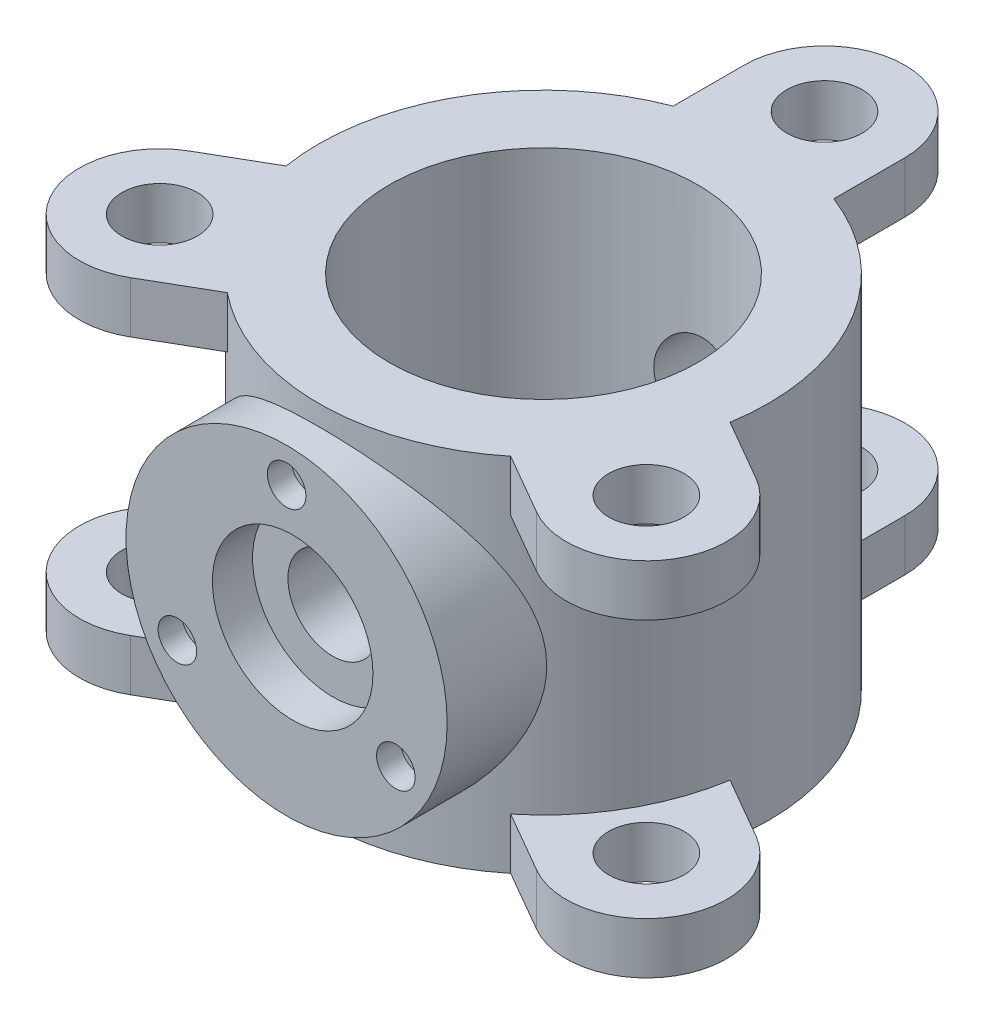
SolidWorks part; units mm, degrees
ref_plane "Front Plane" through (0, 0, 0) normal (0, 0, 1) x (1, 0, 0)
ref_plane "Top Plane" through (0, 0, 0) normal (0, 1, 0) x (1, 0, 0)
ref_plane "Right Plane" through (0, 0, 0) normal (1, 0, 0) x (0, 0, -1)
sketch "Sketch1" plane through (0, 0, 0) normal (0, 1, 0) x (1, 0, 0)
  circle A0 centre (0, 0) radius 96
  circle A1 centre (0, 0) radius 140
  dimension "D1" = 280
  dimension "D2" = 192
extrude "Boss-Extrude1" add sketch "Sketch1" along normal blind 225
sketch "Sketch2" plane through (0, 225, 0) normal (0, 1, 0) x (1, 0, 0)
  line L0 (50, 175) -> (50, 130.767)
  line L1 (-50, 175) -> (-50, 130.767)
  line L2 (50, 130.767) -> (-50, 130.767)
  arc A0 (50, 175) -> (-50, 175) centre (0, 175) ccw
  circle A1 centre (0, 175) radius 23.5
  circle A2 centre (0, 0) radius 140 construction
  dimension "D2" = 100
  dimension "D3" = 47
  dimension "D1" = 175
extrude "Boss-Extrude2" add sketch "Sketch2" against normal blind 32
pattern_circular "CirPattern1" count 3 over 360 about axis through (0, 0, 0) along (0, 1, 0) of "Boss-Extrude2"
ref_plane "Plane1" through (0, 112.5, 0) normal (0, 1, 0) x (1, 0, 0)
mirror "Mirror1" about plane through (0, 112.5, 0) normal (0, 1, 0) of "CirPattern1", "Boss-Extrude2"
ref_plane "Plane2" through (0, 0, 160) normal (0, 0, 1) x (1, 0, 0)
sketch "Sketch3" plane through (0, 0, 160) normal (0, 0, 1) x (1, 0, 0)
  line L0 (126.5544, 0) -> (201.5544, 0) construction
  circle A0 centre (0, 112.5) radius 100
  dimension "D1" = 200
  dimension "D2" = 112.5
extrude "Boss-Extrude3" add sketch "Sketch3" against normal up to surface (62.0204 mm away)
sketch "Sketch4" plane through (0, 0, 160) normal (0, 0, 1) x (1, 0, 0)
  circle A0 centre (3.7786, 116.0425) radius 50
extrude "Cut-Extrude1" cut sketch "Sketch4" against normal blind 25
sketch "Sketch5" plane through (0, 0, 135) normal (0, 0, 1) x (1, 0, 0)
  circle A0 centre (3.7786, 116.0425) radius 28
extrude "Cut-Extrude2" cut sketch "Sketch5" against normal through all
sketch "Sketch7" plane through (0, 0, 160) normal (0, 0, 1) x (1, 0, 0)
  circle A0 centre (0, 191.0425) radius 12
  circle A1 centre (3.7786, 116.0425) radius 50 construction
  dimension "D1" = 24
  dimension "D2" = 75
extrude "Cut-Extrude3" cut sketch "Sketch7" against normal blind 15
pattern_circular "CirPattern2" count 3 over 360 about axis through (0, 112.5, 0) along (0, 0, 1) of "Cut-Extrude3"
